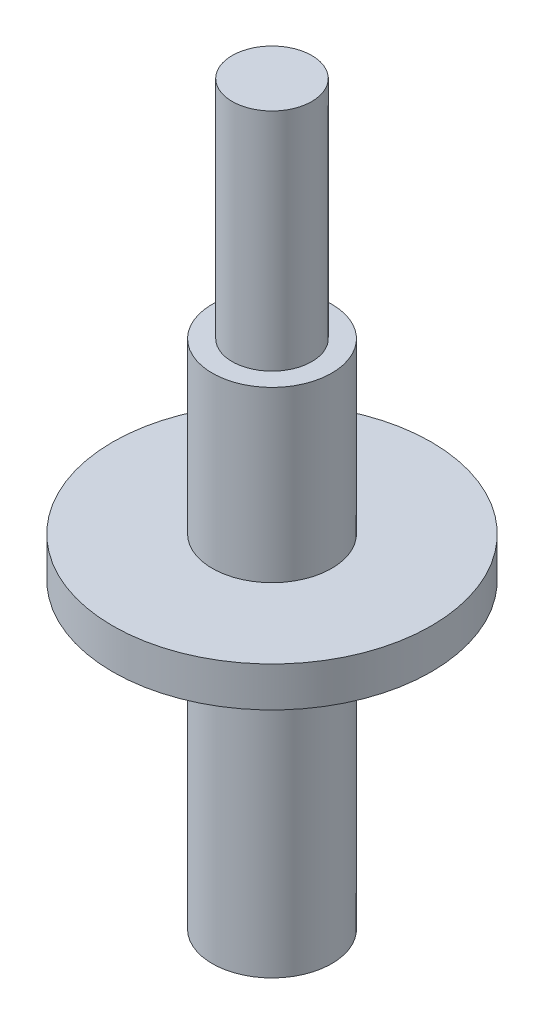
SolidWorks part; units mm, degrees
ref_plane "Front" through (0, 0, 0) normal (0, 0, 1) x (1, 0, 0)
ref_plane "Top" through (0, 0, 0) normal (0, 1, 0) x (1, 0, 0)
ref_plane "Right" through (0, 0, 0) normal (1, 0, 0) x (0, 0, -1)
sketch "Sketch1" plane through (0, 0, 0) normal (0, 0, 1) x (1, 0, 0)
  line L0 (0, 0) -> (0, 37)
  line L1 (0, 37) -> (2, 37)
  line L2 (2, 37) -> (2, 25.6845)
  line L3 (3, 25.6845) -> (2, 25.6845)
  line L4 (3, 25.6845) -> (3, 17.1919)
  line L5 (3, 17.1919) -> (8, 17.1919)
  line L6 (8, 17.1919) -> (8, 15.1919)
  line L7 (8, 15.1919) -> (3, 15.1919)
  line L8 (3, 15.1919) -> (3, 0)
  line L9 (3, 0) -> (0, 0)
  dimension "D1" = 37
  dimension "D2" = 2
  dimension "D3" = 1
  dimension "D4" = 5
  dimension "D5" = 2
revolve "Revolve1" add sketch "Sketch1" angle 360 about L0
sketch "Sketch2" plane through (0, 0, 0) normal (0, -1, 0) x (1, 0, 0)
  circle A0 centre (0, 0) radius 2
  dimension "D1" = 4
extrude "Cut-Extrude1" cut sketch "Sketch2" against normal blind 6
